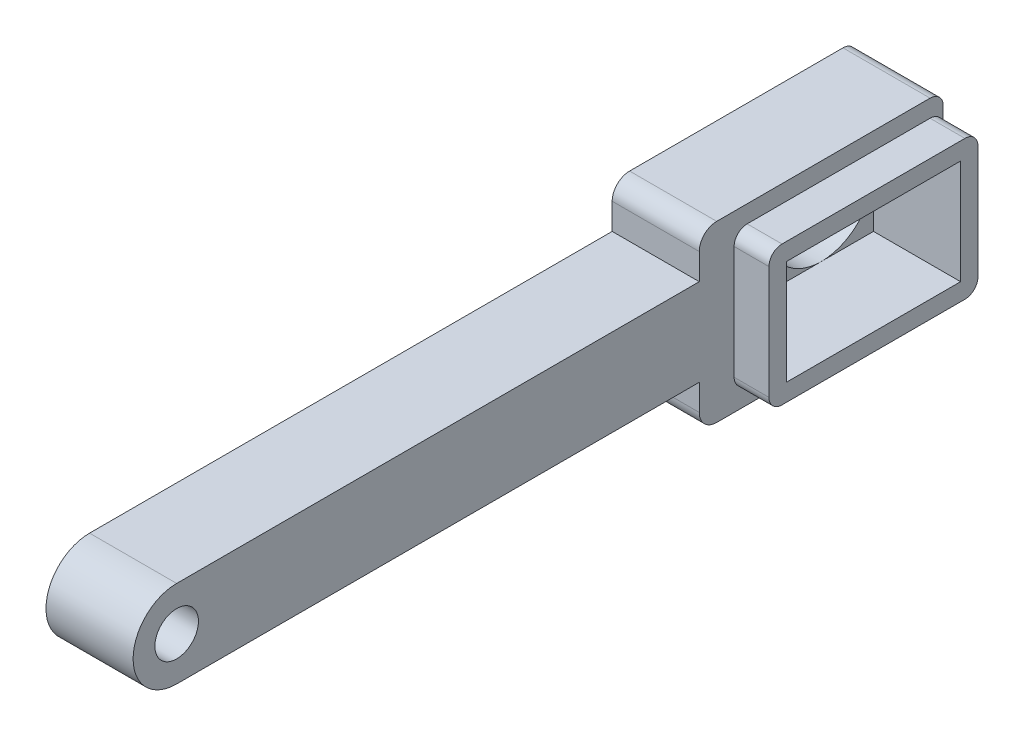
SolidWorks part; units mm, degrees
ref_plane "Plan de face" through (0, 0, 0) normal (0, 0, 1) x (1, 0, 0)
ref_plane "Plan de dessus" through (0, 0, 0) normal (0, 1, 0) x (1, 0, 0)
ref_plane "Plan de droite" through (0, 0, 0) normal (1, 0, 0) x (0, 0, -1)
sketch "Esquisse1" plane through (0, 0, 0) normal (1, 0, 0) x (0, 0, -1)
  line L0 (0, 16.2018) -> (0, -28.6945) construction
  line L1 (-53.9951, 0) -> (93.5695, 0) construction
  line L2 (0, 5) -> (-40, 5)
  line L7 (0, 5) -> (20, 5)
  line L8 (20, 5) -> (20, 8)
  line L9 (22, 10) -> (40, 10)
  line L16 (-40, 16.2018) -> (-40, -11.8174) construction
  line L17 (40, 26.0959) -> (40, -11.8174) construction
  line L18 (22, -10) -> (40, -10)
  line L19 (20, -5) -> (20, -8)
  line L20 (0, -5) -> (20, -5)
  line L21 (0, -5) -> (-40, -5)
  line L22 (40, 10) -> (46.5, 10)
  line L23 (48, 8.5) -> (48, -8.5)
  line L24 (46.5, -10) -> (40, -10)
  arc A4 (-40, 5) -> (-40, -5) centre (-40, 0) ccw
  arc A6 (22, -10) -> (20, -8) centre (22, -8) cw
  arc A7 (20, 8) -> (22, 10) centre (22, 8) cw
  arc A8 (48, -8.5) -> (46.5, -10) centre (46.5, -8.5) cw
  arc A9 (46.5, 10) -> (48, 8.5) centre (46.5, 8.5) cw
  point P24 (20, -10)
  point P27 (20, 10)
  point P32 (48, 10)
  dimension "D1" = 40
  dimension "D3" = 20
  dimension "D6" = 2
  dimension "D8" = 1.5
  dimension "D2" = 40
  dimension "D4" = 5
  dimension "D5" = 10
  dimension "D7" = 8
extrude "Boss.-Extru.1" add sketch "Esquisse1" along normal blind 10
sketch "Esquisse3" plane through (10, 0, 0) normal (1, 0, 0) x (0, 0, -1)
  line L2 (20, 8) -> (20, 5)
  line L10 (20, 8) -> (20, 5)
  line L12 (46.5, 10) -> (22, 10)
  line L14 (46.5, 10) -> (22, 10)
  line L16 (20, 5) -> (-40, 5)
  line L18 (20, 5) -> (-40, 5)
  line L20 (-40, -5) -> (20, -5)
  line L21 (-40, -5) -> (20, -5)
  line L22 (20, -5) -> (20, -8)
  line L23 (20, -5) -> (20, -8)
  line L24 (22, -10) -> (46.5, -10)
  line L25 (22, -10) -> (46.5, -10)
  line L27 (48, -8.5) -> (48, 8.5)
  line L28 (48, -8.5) -> (48, 8.5)
  circle A0 centre (-40, 0) radius 2.5
  arc A2 (46.5, -10) -> (48, -8.5) centre (46.5, -8.5) ccw
  arc A9 (-40, 5) -> (-40, -5) centre (-40, 0) ccw
  arc A10 (-40, 5) -> (-40, -5) centre (-40, 0) ccw
  arc A13 (22, 10) -> (20, 8) centre (22, 8) ccw
  arc A14 (22, 10) -> (20, 8) centre (22, 8) ccw
  arc A15 (20, -8) -> (22, -10) centre (22, -8) ccw
  arc A16 (20, -8) -> (22, -10) centre (22, -8) ccw
  arc A18 (46.5, -10) -> (48, -8.5) centre (46.5, -8.5) ccw
  arc A19 (48, 8.5) -> (46.5, 10) centre (46.5, 8.5) ccw
  arc A20 (48, 8.5) -> (46.5, 10) centre (46.5, 8.5) ccw
  dimension "D2" = 5
  dimension "D1" = 0
extrude "Enlèv. mat.-Extru.1" cut sketch "Esquisse3" against normal blind 5 contours A0
sketch "Esquisse4" plane through (10, 0, 0) normal (1, 0, 0) x (0, 0, -1)
  line L0 (0, 0) -> (57.1604, 0) construction
  line L2 (20, 8) -> (20, 5)
  line L10 (20, 8) -> (20, 5)
  line L12 (46.5, 10) -> (22, 10)
  line L14 (46.5, 10) -> (22, 10)
  line L16 (20, 5) -> (-40, 5)
  line L18 (20, 5) -> (-40, 5)
  line L20 (-40, -5) -> (20, -5)
  line L21 (-40, -5) -> (20, -5)
  line L22 (20, -5) -> (20, -8)
  line L23 (20, -5) -> (20, -8)
  line L24 (22, -10) -> (46.5, -10)
  line L25 (22, -10) -> (46.5, -10)
  line L28 (48, -8.5) -> (48, 8.5)
  line L29 (48, -8.5) -> (48, 8.5)
  arc A1 (35.3333, 3.7712) -> (35.3333, -3.7712) centre (40, 0) cw
  arc A2 (46.5, -10) -> (48, -8.5) centre (46.5, -8.5) ccw
  arc A6 (35.3333, 3.7712) -> (35.3333, -3.7712) centre (40, 0) ccw construction
  arc A9 (-40, 5) -> (-40, -5) centre (-40, 0) ccw
  arc A10 (-40, 5) -> (-40, -5) centre (-40, 0) ccw
  arc A11 (35.3333, 3.7712) -> (35.3333, -3.7712) centre (34, 0) ccw
  arc A13 (22, 10) -> (20, 8) centre (22, 8) ccw
  arc A14 (22, 10) -> (20, 8) centre (22, 8) ccw
  arc A15 (20, -8) -> (22, -10) centre (22, -8) ccw
  arc A16 (20, -8) -> (22, -10) centre (22, -8) ccw
  arc A27 (46.5, -10) -> (48, -8.5) centre (46.5, -8.5) ccw
  arc A28 (48, 8.5) -> (46.5, 10) centre (46.5, 8.5) ccw
  arc A29 (48, 8.5) -> (46.5, 10) centre (46.5, 8.5) ccw
  dimension "D2" = 4
  dimension "D3" = 6
  dimension "D4" = 40
  dimension "D1" = 0
extrude "Enlèv. mat.-Extru.3" cut sketch "Esquisse4" against normal through all both contours A1 A11
sketch "Esquisse6" plane through (10, 0, 0) normal (1, 0, 0) x (0, 0, -1)
  line L0 (26, 6) -> (46, 6)
  line L1 (46, 6) -> (46, -6)
  line L2 (46, -6) -> (26, -6)
  line L3 (26, -6) -> (26, 6)
  line L6 (46.5, 10) -> (22, 10)
  line L7 (20, 8) -> (20, 5)
  line L8 (20, 5) -> (-40, 5)
  line L9 (-40, -5) -> (20, -5)
  line L10 (20, -5) -> (20, -8)
  line L11 (22, -10) -> (46.5, -10)
  line L12 (46.5, 10) -> (22, 10)
  line L13 (20, 8) -> (20, 5)
  line L14 (20, 5) -> (-40, 5)
  line L15 (-40, -5) -> (20, -5)
  line L16 (20, -5) -> (20, -8)
  line L17 (22, -10) -> (46.5, -10)
  line L24 (48, -8.5) -> (48, 8.5)
  line L25 (48, -8.5) -> (48, 8.5)
  arc A0 (35.3333, -3.7712) -> (35.3333, 3.7712) centre (40, 0) ccw construction
  arc A5 (22, 10) -> (20, 8) centre (22, 8) ccw
  arc A6 (-40, 5) -> (-40, -5) centre (-40, 0) ccw
  arc A7 (20, -8) -> (22, -10) centre (22, -8) ccw
  arc A9 (22, 10) -> (20, 8) centre (22, 8) ccw
  arc A10 (-40, 5) -> (-40, -5) centre (-40, 0) ccw
  arc A11 (20, -8) -> (22, -10) centre (22, -8) ccw
  arc A28 (48, 8.5) -> (46.5, 10) centre (46.5, 8.5) ccw
  arc A29 (48, 8.5) -> (46.5, 10) centre (46.5, 8.5) ccw
  arc A30 (46.5, -10) -> (48, -8.5) centre (46.5, -8.5) ccw
  arc A31 (46.5, -10) -> (48, -8.5) centre (46.5, -8.5) ccw
  dimension "D2" = 20
  dimension "D1" = 0
extrude "Enlèv. mat.-Extru.4" cut sketch "Esquisse6" against normal blind 6 contours L3 L0 L1 L2
sketch "Esquisse7" plane through (10, 0, 0) normal (1, 0, 0) x (0, 0, -1)
  line L0 (24, 6.5) -> (24, -6.5)
  line L1 (25.5, -8) -> (46.5, -8)
  line L2 (48, -6.5) -> (48, 6.5)
  line L3 (46.5, 8) -> (25.5, 8)
  line L4 (0, 0) -> (64.6111, 0) construction
  line L5 (26, 6) -> (46, 6) construction
  line L6 (26, -6) -> (26, 6) construction
  line L7 (46, 6) -> (46, -6) construction
  line L15 (-40, -5) -> (20, -5)
  line L16 (20, -5) -> (20, -8)
  line L17 (22, -10) -> (46.5, -10)
  line L18 (48, -8.5) -> (48, 8.5)
  line L19 (46.5, 10) -> (22, 10)
  line L20 (20, 8) -> (20, 5)
  line L21 (20, 5) -> (-40, 5)
  line L22 (-40, -5) -> (20, -5)
  line L23 (20, -5) -> (20, -8)
  line L24 (22, -10) -> (46.5, -10)
  line L25 (48, -8.5) -> (48, 8.5)
  line L26 (46.5, 10) -> (22, 10)
  line L27 (20, 8) -> (20, 5)
  line L28 (20, 5) -> (-40, 5)
  arc A0 (46.5, -8) -> (48, -6.5) centre (46.5, -6.5) ccw
  arc A1 (48, 6.5) -> (46.5, 8) centre (46.5, 6.5) ccw
  arc A2 (24, -6.5) -> (25.5, -8) centre (25.5, -6.5) ccw
  arc A3 (25.5, 8) -> (24, 6.5) centre (25.5, 6.5) ccw
  arc A7 (-40, 5) -> (-40, -5) centre (-40, 0) ccw
  arc A10 (20, -8) -> (22, -10) centre (22, -8) ccw
  arc A11 (46.5, -10) -> (48, -8.5) centre (46.5, -8.5) ccw
  arc A12 (48, 8.5) -> (46.5, 10) centre (46.5, 8.5) ccw
  arc A13 (22, 10) -> (20, 8) centre (22, 8) ccw
  arc A14 (-40, 5) -> (-40, -5) centre (-40, 0) ccw
  arc A17 (20, -8) -> (22, -10) centre (22, -8) ccw
  arc A18 (46.5, -10) -> (48, -8.5) centre (46.5, -8.5) ccw
  arc A19 (48, 8.5) -> (46.5, 10) centre (46.5, 8.5) ccw
  arc A20 (22, 10) -> (20, 8) centre (22, 8) ccw
  line M17 (26, -6) -> (26, 6)
  line M18 (26, 6) -> (46, 6)
  line M19 (46, 6) -> (46, -6)
  line M20 (46, -6) -> (26, -6)
  line M26 (48, -8.5) -> (48, 8.5)
  dimension "D5" = 1.5
  dimension "D1" = 2
  dimension "D2" = 2
  dimension "D3" = 2
  dimension "D4" = 0
extrude "Boss.-Extru.4" add sketch "Esquisse7" along normal blind 4 contours L0 L4 L25 L3 M17 M18 M19 | L4 L0 L1 M26 M19 M20 M17
